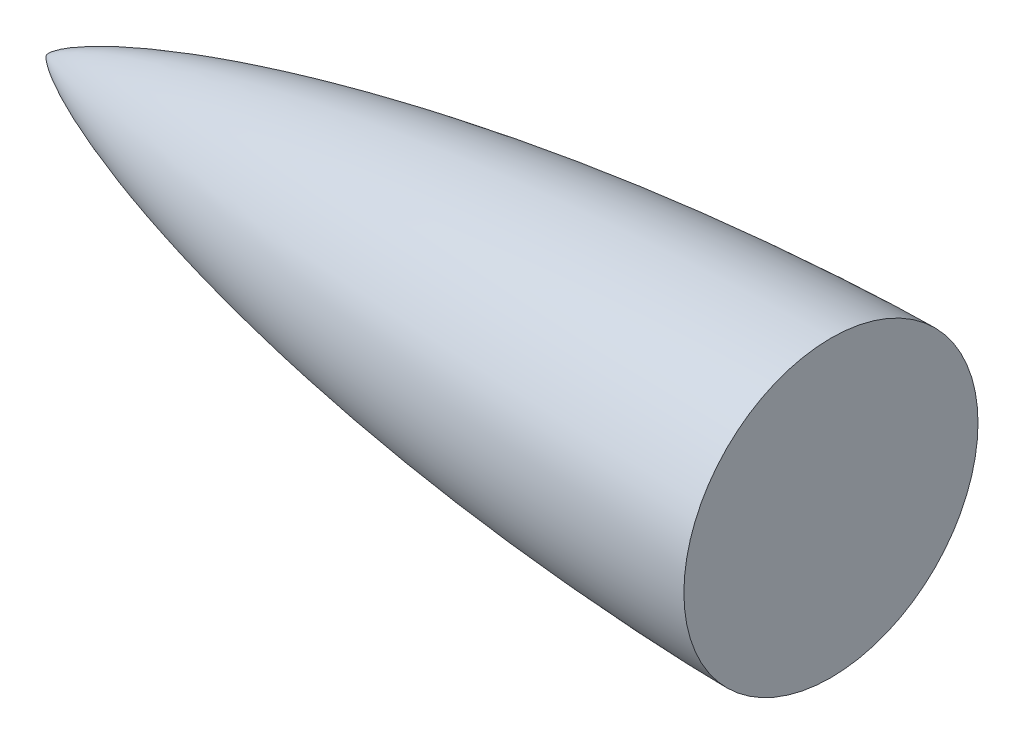
SolidWorks part; units mm, degrees
ref_plane "Front Plane" through (0, 0, 0) normal (0, 0, 1) x (1, 0, 0)
ref_plane "Top Plane" through (0, 0, 0) normal (0, 1, 0) x (1, 0, 0)
ref_plane "Right Plane" through (0, 0, 0) normal (1, 0, 0) x (0, 0, -1)
sketch "Sketch5" plane through (0, 0, 0) normal (0, 0, 1) x (1, 0, 0)
  line L0 (0, 0) -> (16, 0)
  line L1 (16, 0) -> (16, 3)
  spline S0 degree 4 poles (0, 0) (0.0011, 0.0038) (0.0036, 0.0097) (0.0086, 0.0172) (0.0169, 0.0284) (0.0284, 0.0418) (0.0476, 0.0616) (0.0809, 0.0916) (0.1384, 0.1369) (0.2365, 0.2041) (0.397, 0.2999) (0.6589, 0.4358) (1.0521, 0.613) (1.6433, 0.845) (2.4124, 1.1051) (3.3153, 1.3703) (4.3114, 1.6257) (5.3143, 1.8524) (6.3226, 2.0543) (7.3351, 2.2336) (8.351, 2.3923) (9.3697, 2.5316) (10.3908, 2.6526) (11.4138, 2.7558) (12.4384, 2.8421) (13.4642, 2.9113) (14.4829, 2.9633) (15.2454, 2.9887) (15.7512, 2.9987) (16, 3) knots 0 0 0 0 0 0.000954 0.001562 0.002178 0.003399 0.005244 0.008276 0.013078 0.021202 0.034173 0.053734 0.084848 0.126138 0.1887 0.251262 0.313823 0.376385 0.438947 0.501508 0.56407 0.626632 0.689193 0.751755 0.814317 0.876879 0.93944 1 1 1 1 1 construction
  spline S1 degree 4 poles (0, 0) (0.0011, 0.0038) (0.0036, 0.0097) (0.0086, 0.0172) (0.0169, 0.0284) (0.0284, 0.0418) (0.0476, 0.0616) (0.0809, 0.0916) (0.1384, 0.1369) (0.2365, 0.2041) (0.397, 0.2999) (0.6589, 0.4358) (1.0521, 0.613) (1.6433, 0.845) (2.4124, 1.1051) (3.3153, 1.3703) (4.3114, 1.6257) (5.3143, 1.8524) (6.3226, 2.0543) (7.3351, 2.2336) (8.351, 2.3923) (9.3697, 2.5316) (10.3908, 2.6526) (11.4138, 2.7558) (12.4384, 2.8421) (13.4642, 2.9113) (14.4829, 2.9633) (15.2454, 2.9887) (15.7512, 2.9987) (16, 3) knots 0 0 0 0 0 0.000954 0.001562 0.002178 0.003399 0.005244 0.008276 0.013078 0.021202 0.034173 0.053734 0.084848 0.126138 0.1887 0.251262 0.313823 0.376385 0.438947 0.501508 0.56407 0.626632 0.689193 0.751755 0.814317 0.876879 0.93944 1 1 1 1 1
  dimension "D1" = 16
revolve "Revolve5" add sketch "Sketch5" angle 360 about L0
